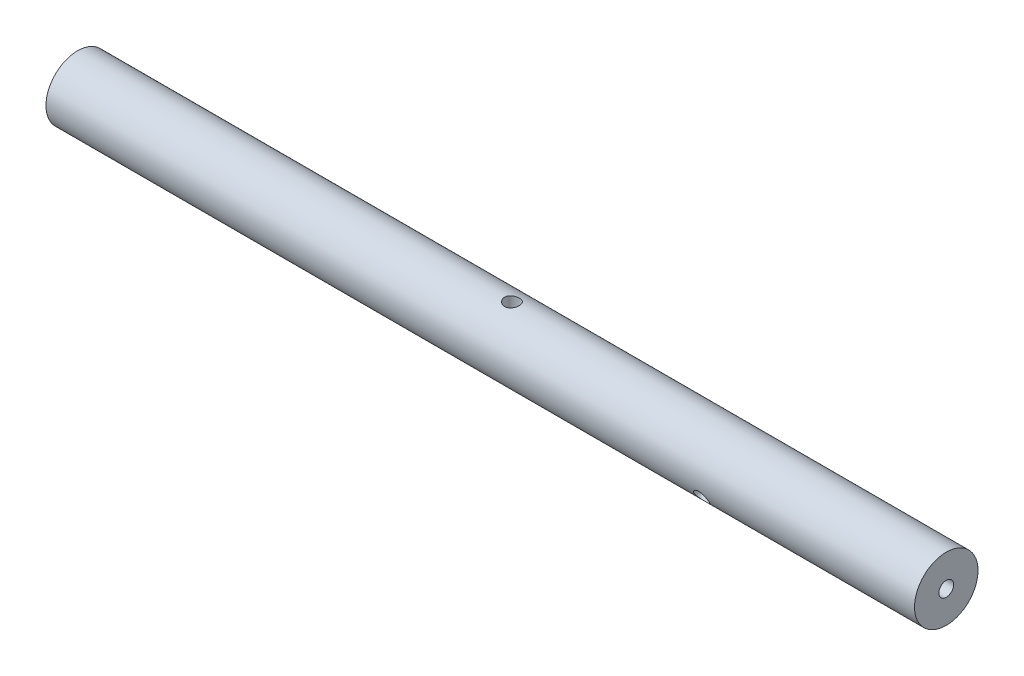
SolidWorks part; units mm, degrees
material "Brass"
ref_plane "Front Plane" through (0, 0, 0) normal (0, 0, 1) x (1, 0, 0)
ref_plane "Top Plane" through (0, 0, 0) normal (0, 1, 0) x (1, 0, 0)
ref_plane "Right Plane" through (0, 0, 0) normal (1, 0, 0) x (0, 0, -1)
sketch "Sketch1" plane through (0, 0, 0) normal (1, 0, 0) x (0, 0, -1)
  circle A0 centre (0, 0) radius 11.11
  dimension "D1" = 22.22
extrude "Boss-Extrude1" add sketch "Sketch1" along normal blind 304
hole_wizard "Ø3.0 (3) Diameter Hole2" positions "Sketch7" profile "Sketch6" hole size "Ø3.0" standard "ANSI Metric"
sketch "Sketch7" plane through (0, 0, 0) normal (-1, 0, 0) x (0, 0, 1)
  point P0 (0, 5.3)
  dimension "D1" = 5.3
sketch "Sketch6" plane through (0, 5.3, 0) normal (0, 1, 0) x (0, 0, 1)
  line L0 (0, 0) -> (0, 11.9013)
  line L1 (0, 11.9013) -> (1.5, 11)
  line L2 (1.5, 11) -> (1.5, 0)
  line L5 (1.5, 0) -> (0, 0)
  line L10 (0, 11.9013) -> (-1.5, 11) construction
  line L11 (0, -6.35) -> (0, 107.95) construction
  dimension "Hole Dia." = 3
  dimension "Hole Depth" = 11
  dimension "Drill Angle" = 118
ref_plane "Plane1" through (0, 11.11, 0) normal (0, 1, 0) x (1, 0, 0)
hole_wizard "13/64 (0.20313) Diameter Hole2" positions "Sketch11" profile "Sketch10" hole size "13/64" standard "ANSI Inch"
sketch "Sketch11" plane through (0, 11.11, 0) normal (0, 1, 0) x (1, 0, 0)
  point P1 (152, 0)
  dimension "D1" = 152
sketch "Sketch10" plane through (152, 11.11, 0) normal (1, 0, 0) x (0, 0, 1)
  line L0 (0, 0) -> (0, 8.5501)
  line L1 (0, 8.5501) -> (2.5798, 7)
  line L2 (2.5798, 7) -> (2.5798, 0)
  line L5 (2.5798, 0) -> (0, 0)
  line L10 (0, 8.5501) -> (-2.5798, 7) construction
  line L11 (0, -6.35) -> (0, 107.95) construction
  dimension "Hole Dia." = 5.1595
  dimension "Hole Depth" = 7
  dimension "Drill Angle" = 118
ref_plane "Plane2" through (0, -5.555, 9.6215) normal (0, -0.5, 0.866) x (-1, 0, 0)
ref_plane "Plane3" through (0, -5.555, -9.6215) normal (0, -0.5, -0.866) x (-1, 0, 0)
hole_wizard "13/64 (0.20313) Diameter Hole4" positions "Sketch15" profile "Sketch14" hole size "13/64" standard "ANSI Inch"
sketch "Sketch15" plane through (0, -5.555, -9.6215) normal (0, -0.5, -0.866) x (-1, 0, 0)
  point P0 (-76, 0)
  dimension "D1" = 76
sketch "Sketch14" plane through (76, -5.555, -9.6215) normal (1, 0, 0) x (0, 0.866, -0.5)
  line L0 (0, 0) -> (0, 8.5501)
  line L1 (0, 8.5501) -> (2.5798, 7)
  line L2 (2.5798, 7) -> (2.5798, 0)
  line L5 (2.5798, 0) -> (0, 0)
  line L10 (0, 8.5501) -> (-2.5798, 7) construction
  line L11 (0, -6.35) -> (0, 107.95) construction
  dimension "Hole Dia." = 5.1595
  dimension "Hole Depth" = 7
  dimension "Drill Angle" = 118
hole_wizard "13/64 (0.20313) Diameter Hole5" positions "Sketch17" profile "Sketch16" hole size "13/64" standard "ANSI Inch"
sketch "Sketch17" plane through (0, -5.555, 9.6215) normal (0, -0.5, 0.866) x (-1, 0, 0)
  point P0 (-228, 0)
  dimension "D1" = 228
sketch "Sketch16" plane through (228, -5.555, 9.6215) normal (1, 0, 0) x (0, -0.866, -0.5)
  line L0 (0, 0) -> (0, 8.5501)
  line L1 (0, 8.5501) -> (2.5798, 7)
  line L2 (2.5798, 7) -> (2.5798, 0)
  line L5 (2.5798, 0) -> (0, 0)
  line L10 (0, 8.5501) -> (-2.5798, 7) construction
  line L11 (0, -6.35) -> (0, 107.95) construction
  dimension "Hole Dia." = 5.1595
  dimension "Hole Depth" = 7
  dimension "Drill Angle" = 118
hole_wizard "13/64 (0.20313) Diameter Hole6" positions "Sketch19" profile "Sketch18" hole size "13/64" standard "ANSI Inch"
sketch "Sketch19" plane through (304, 0, 0) normal (1, 0, 0) x (0, 0, -1)
  point P0 (0, 0)
sketch "Sketch18" plane through (304, 0, 0) normal (0, 1, 0) x (0, 0, -1)
  line L0 (0, 0) -> (0, 8.5501)
  line L1 (0, 8.5501) -> (2.5798, 7)
  line L2 (2.5798, 7) -> (2.5798, 0)
  line L5 (2.5798, 0) -> (0, 0)
  line L10 (0, 8.5501) -> (-2.5798, 7) construction
  line L11 (0, -6.35) -> (0, 107.95) construction
  dimension "Hole Dia." = 5.1595
  dimension "Hole Depth" = 7
  dimension "Drill Angle" = 118
